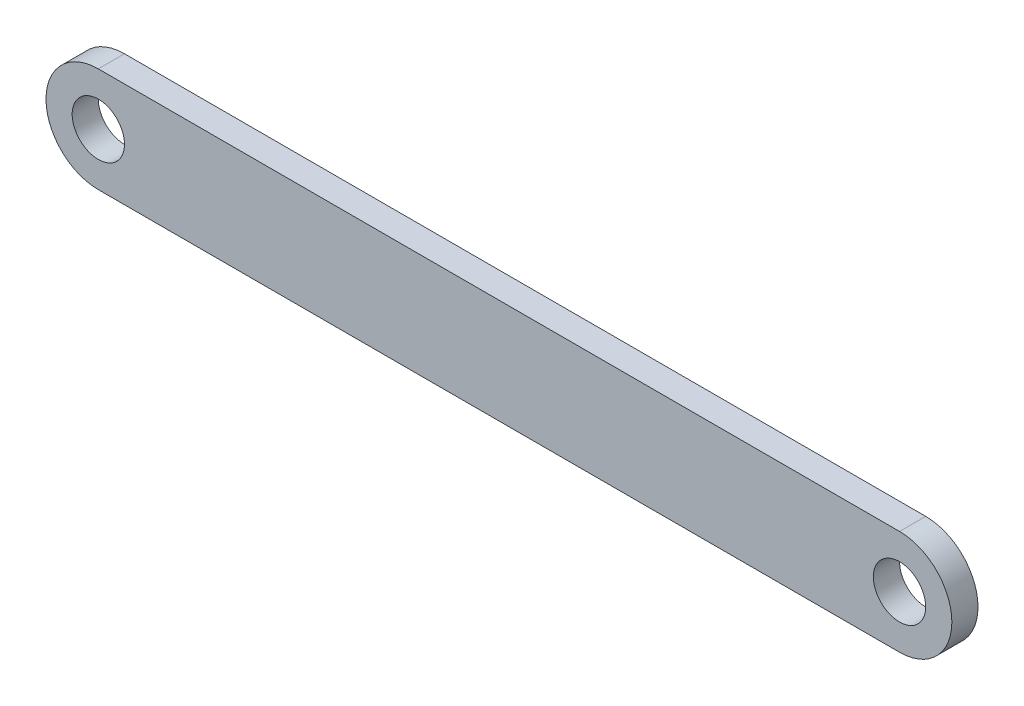
SolidWorks part; units mm, degrees
ref_plane "Plano frontal" through (0, 0, 0) normal (0, 0, 1) x (1, 0, 0)
ref_plane "Plano superior" through (0, 0, 0) normal (0, 1, 0) x (1, 0, 0)
ref_plane "Plano direito" through (0, 0, 0) normal (1, 0, 0) x (0, 0, -1)
sketch "Esboço1" plane through (0, 0, 0) normal (0, 0, 1) x (1, 0, 0)
  line L0 (-15.315, 2) -> (15.315, 2)
  line L1 (-15.315, 0) -> (15.315, 0) construction
  line L2 (-15.315, -2) -> (15.315, -2)
  arc A0 (-15.315, 2) -> (-15.315, -2) centre (-15.315, 0) ccw
  arc A1 (15.315, 2) -> (15.315, -2) centre (15.315, 0) cw
  circle A2 centre (-15.315, 0) radius 1
  circle A3 centre (15.315, 0) radius 1
  point P3 (0, 2)
  dimension "D3" = 2
  dimension "D1" = 30.63
  dimension "D2" = 2
extrude "Ressalto-extrusão1" add sketch "Esboço1" along normal blind 1
